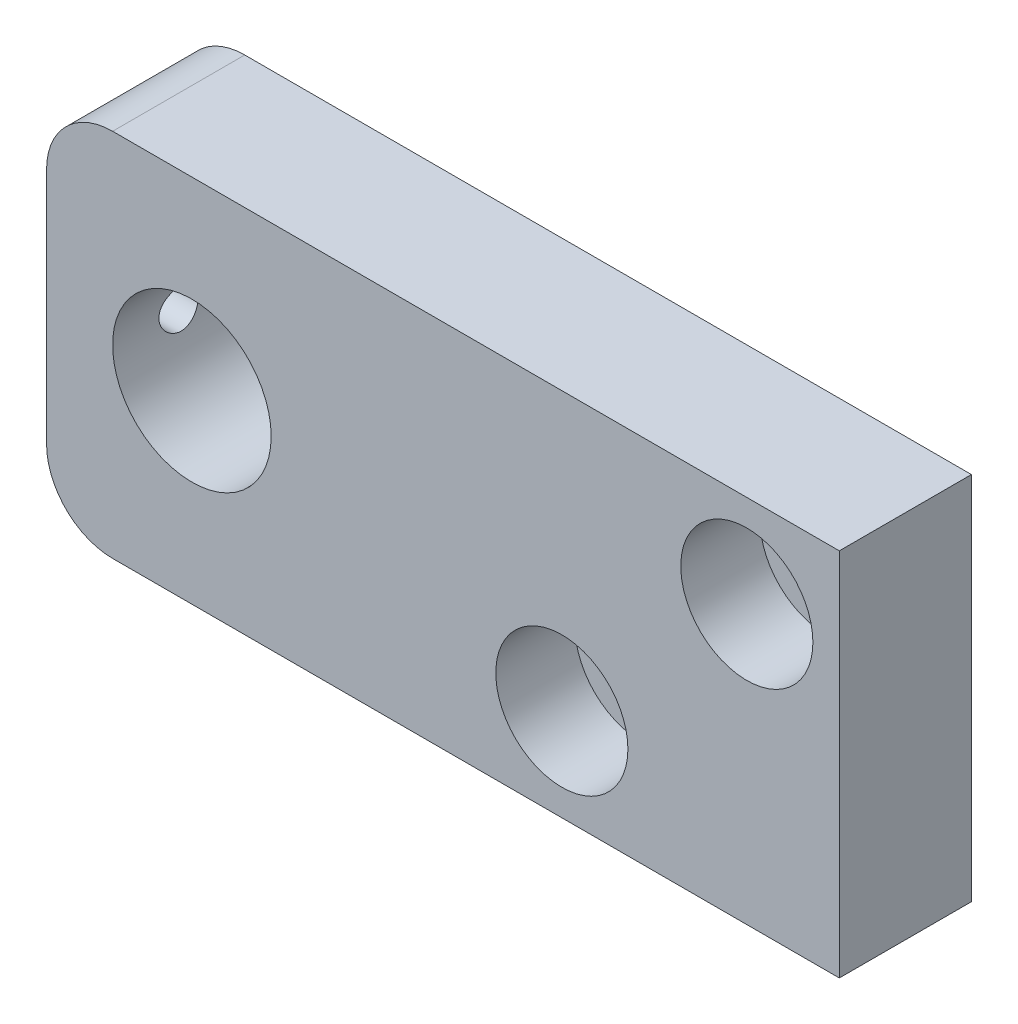
SolidWorks part; units mm, degrees
ref_plane "Ön Düzlem" through (0, 0, 0) normal (0, 0, 1) x (1, 0, 0)
ref_plane "Üst Düzlem" through (0, 0, 0) normal (0, 1, 0) x (1, 0, 0)
ref_plane "Sağ Düzlem" through (0, 0, 0) normal (1, 0, 0) x (0, 0, -1)
sketch "Çizim1" plane through (0, 0, 0) normal (0, 0, 1) x (1, 0, 0)
  line L1 (30, -14) -> (-25, -14)
  line L2 (30, -14) -> (30, 14)
  line L3 (30, 14) -> (-25, 14)
  line L4 (-30, -9) -> (-30, 9)
  line L5 (30, -14) -> (-30, 14) construction
  line L6 (30, 14) -> (-30, -14) construction
  line L7 (9, -7) -> (23, -7) construction
  line L8 (9, -7) -> (9, 7) construction
  line L9 (9, 7) -> (23, 7) construction
  line L10 (23, -7) -> (23, 7) construction
  line L11 (9, -7) -> (23, 7) construction
  line L12 (9, 7) -> (23, -7) construction
  arc A0 (-25, -14) -> (-30, -9) centre (-25, -9) cw
  arc A1 (-25, 14) -> (-30, 9) centre (-25, 9) ccw
  circle A2 centre (23, 7) radius 3
  circle A4 centre (-19, 0) radius 6
  circle A6 centre (9, -7) radius 3
  point P0 (0, 0)
  point P15 (16, 0)
  point P22 (30, 0)
  dimension "D2" = 5
  dimension "D4" = 14
  dimension "D5" = 6
  dimension "D6" = 14
  dimension "D8" = 12
  dimension "D1" = 60
  dimension "D3" = 28
  dimension "D7" = 35
extrude "Yükseklik-Ekstrüzyon1" add sketch "Çizim1" along normal blind 10
sketch "Çizim2" plane through (-30, 0, 0) normal (-1, 0, 0) x (0, 0, 1)
  line L0 (0, 9) -> (10, 9) construction
  circle A0 centre (5, 0) radius 1.5
  point P7 (5, 9)
  dimension "D1" = 3
extrude "Kes-Ekstrüzyon1" cut sketch "Çizim2" against normal up to next
sketch "Sketch1" plane through (0, 0, 10) normal (0, 0, 1) x (1, 0, 0)
  circle A0 centre (9, -7) radius 5
  circle A1 centre (23, 7) radius 5
  dimension "D1" = 10
  dimension "D2" = 10
extrude "Cut-Extrude1" cut sketch "Sketch1" against normal blind 6
